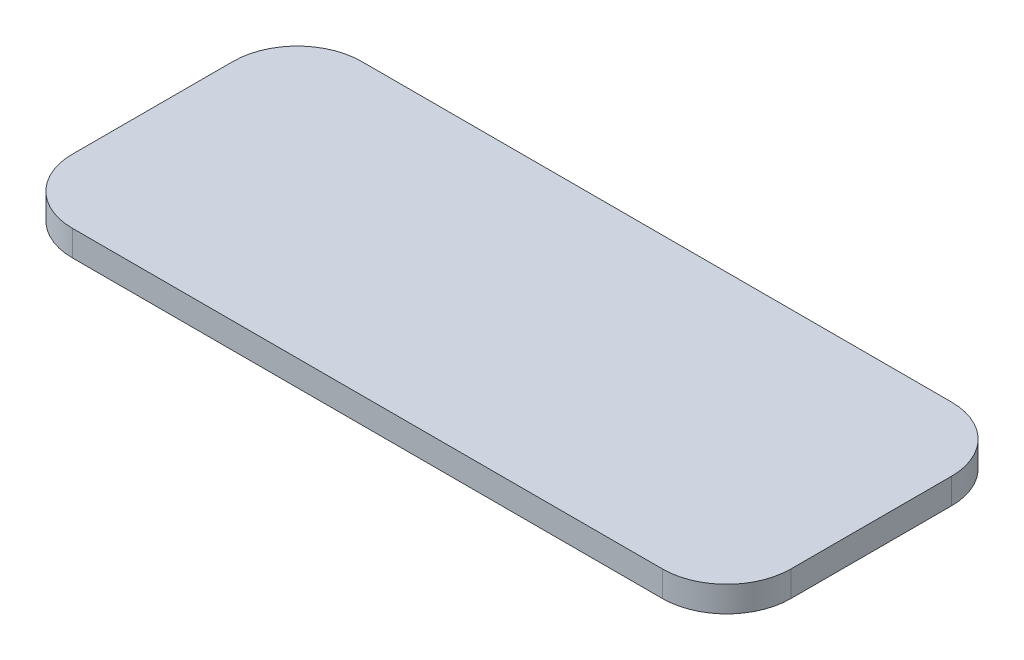
SolidWorks part; units mm, degrees
ref_plane "Front Plane" through (0, 0, 0) normal (0, 0, 1) x (1, 0, 0)
ref_plane "Top Plane" through (0, 0, 0) normal (0, 1, 0) x (1, 0, 0)
ref_plane "Right Plane" through (0, 0, 0) normal (1, 0, 0) x (0, 0, -1)
sketch "Sketch2" plane through (0, 0, 0) normal (0, 1, 0) x (1, 0, 0)
  line L1 (-16.1209, 4.0315) -> (29.835, 4.0315)
  line L2 (-21.1209, -0.9685) -> (-21.1209, -13.4833)
  line L3 (-16.1209, -18.4833) -> (29.835, -18.4833)
  line L4 (34.835, -0.9685) -> (34.835, -13.4833)
  arc A0 (34.835, -13.4833) -> (29.835, -18.4833) centre (29.835, -13.4833) cw
  arc A1 (29.835, 4.0315) -> (34.835, -0.9685) centre (29.835, -0.9685) cw
  arc A2 (-21.1209, -13.4833) -> (-16.1209, -18.4833) centre (-16.1209, -13.4833) ccw
  arc A3 (-21.1209, -0.9685) -> (-16.1209, 4.0315) centre (-16.1209, -0.9685) cw
  dimension "D1" = 5
extrude "Boss-Extrude1" add sketch "Sketch2" along normal blind 2
